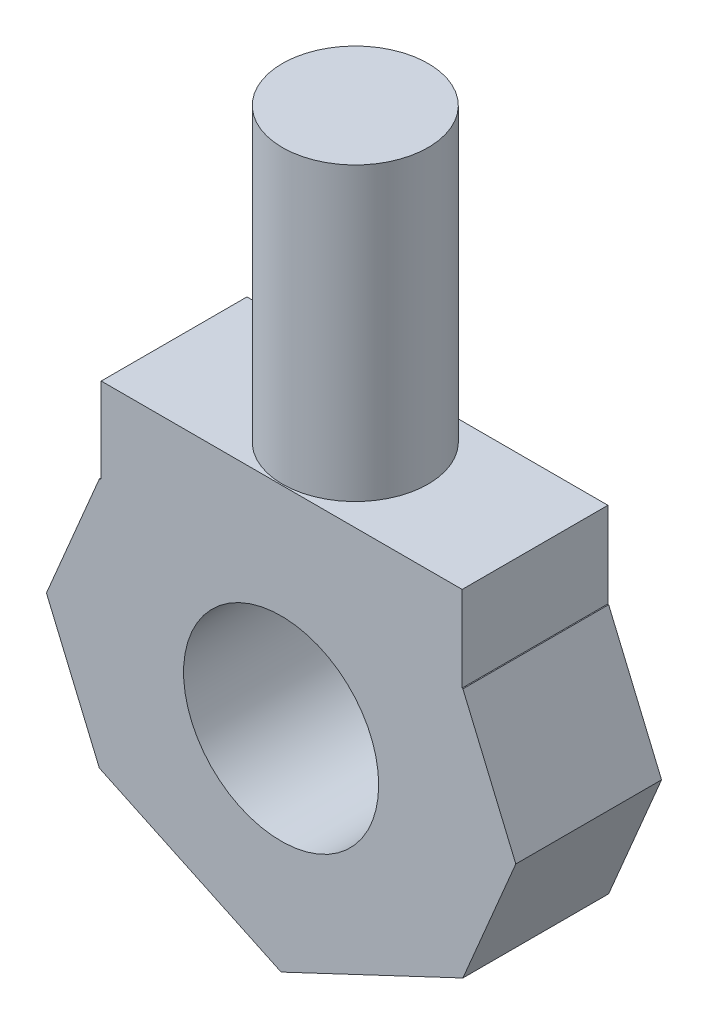
SolidWorks part; units mm, degrees
ref_plane "Front Plane" through (0, 0, 0) normal (0, 0, 1) x (1, 0, 0)
ref_plane "Top Plane" through (0, 0, 0) normal (0, 1, 0) x (1, 0, 0)
ref_plane "Right Plane" through (0, 0, 0) normal (1, 0, 0) x (0, 0, -1)
sketch "Sketch1" plane through (0, 0, 0) normal (0, 0, 1) x (1, 0, 0)
  line L5 (0, -28.948) -> (0, 0) construction
  line L6 (-12.4716, -23.0644) -> (-16.1023, -14.474)
  line L7 (0, -14.474) -> (-25.2152, -14.474) construction
  line L8 (-12.4716, -5.8836) -> (-16.1023, -14.474)
  line L9 (-12.4716, -23.0644) -> (0, -28.948)
  line L10 (-12.4716, -5.8836) -> (0, 0)
  line L11 (12.4716, -5.8836) -> (0, 0)
  line L12 (12.4716, -5.8836) -> (16.1023, -14.474)
  line L13 (12.4716, -23.0644) -> (0, -28.948)
  line L14 (12.4716, -23.0644) -> (16.1023, -14.474)
  circle A0 centre (0, -14.474) radius 6.6945
extrude "Boss-Extrude1" add sketch "Sketch1" along normal blind 10
sketch "Sketch2" plane through (0, 0, 0) normal (0, 1, 0) x (1, 0, 0)
  line L0 (0, 0) -> (-12.4716, 0) construction
  line L5 (-12.3435, 0) -> (12.422, 0)
  line L6 (-12.3435, 0) -> (-12.3435, -10)
  line L7 (-12.3435, -10) -> (12.422, -10)
  line L8 (12.422, 0) -> (12.422, -10)
  line L9 (12.4716, -10) -> (0, -10) construction
extrude "Boss-Extrude2" add sketch "Sketch2" against normal blind 7
sketch "Sketch4" plane through (0, 0, 0) normal (0, 1, 0) x (1, 0, 0)
  circle A0 centre (0, -4.9127) radius 5
  dimension "D1" = 10
extrude "Boss-Extrude4" add sketch "Sketch4" along normal blind 20
